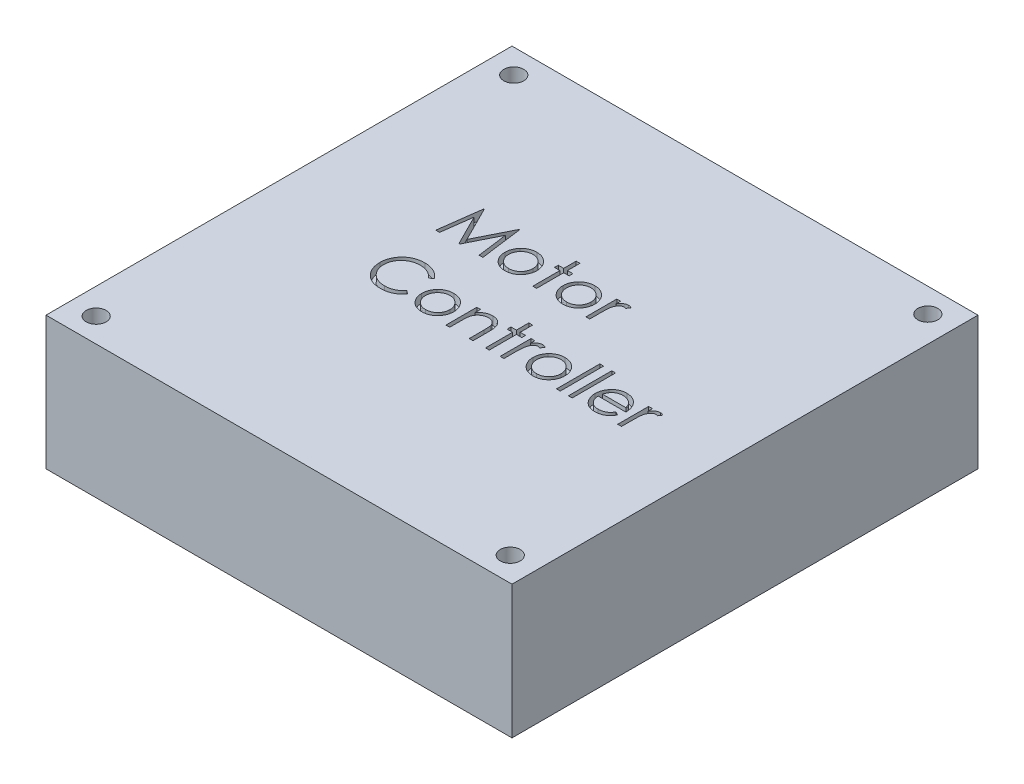
SolidWorks part; units mm, degrees
ref_plane "Front Plane" through (0, 0, 0) normal (0, 0, 1) x (1, 0, 0)
ref_plane "Top Plane" through (0, 0, 0) normal (0, 1, 0) x (1, 0, 0)
ref_plane "Right Plane" through (0, 0, 0) normal (1, 0, 0) x (0, 0, -1)
sketch "Sketch1" plane through (0, 0, 0) normal (0, 1, 0) x (1, 0, 0)
  line L1 (-35, -35) -> (35, -35)
  line L2 (-35, -35) -> (-35, 35)
  line L3 (-35, 35) -> (35, 35)
  line L4 (35, -35) -> (35, 35)
  line L5 (-35, -35) -> (35, 35) construction
  line L6 (-35, 35) -> (35, -35) construction
  point P0 (0, 0)
  dimension "D1" = 70
  dimension "D2" = 70
extrude "Boss-Extrude1" add sketch "Sketch1" along normal blind 20
sketch "Sketch2" plane through (0, 20, 0) normal (0, 1, 0) x (1, 0, 0)
  text T0 "Motor\r\nController" font "Century Gothic" height in points 24
extrude "Cut-Extrude1" cut sketch "Sketch2" against normal blind 1.27
hole_wizard "Ø3.0mm Dowel Hole1" positions "Sketch4" profile "Sketch5" hole size "Ø3.0" standard "ANSI Metric" end condition through all
sketch "Sketch4" plane through (0, 20, 0) normal (0, 1, 0) x (1, 0, 0)
  line L1 (-35, 35) -> (-35, -35) construction
  line L2 (-31.1, -31.365) -> (-31.1, -35) construction
  line L3 (-35, -35) -> (35, -35) construction
  line L6 (-31.1, 31.365) -> (-31.1, 35) construction
  line L7 (35, 35) -> (-35, 35) construction
  line L10 (-31.1, 31.365) -> (-35, 31.365) construction
  line L13 (31.1, 31.365) -> (35, 31.365) construction
  line L14 (35, -35) -> (35, 35) construction
  point P0 (-31.1, 31.365)
  point P2 (31.1, 31.365)
  point P4 (31.1, -31.365)
  point P6 (-31.1, -31.365)
  dimension "D1" = 62.73
  dimension "D2" = 62.2
sketch "Sketch5" plane through (-31.1, 20, -31.365) normal (1, 0, 0) x (0, 0, 1)
  line L0 (0, 0) -> (0, 20)
  line L1 (0, 20) -> (1.5, 20)
  line L2 (1.5, 20) -> (1.5, 0)
  line L5 (1.5, 0) -> (0, 0)
  line L11 (0, -6.35) -> (0, 107.95) construction
  dimension "Thru Hole Dia." = 3
  dimension "Thru Hole Depth" = 20
